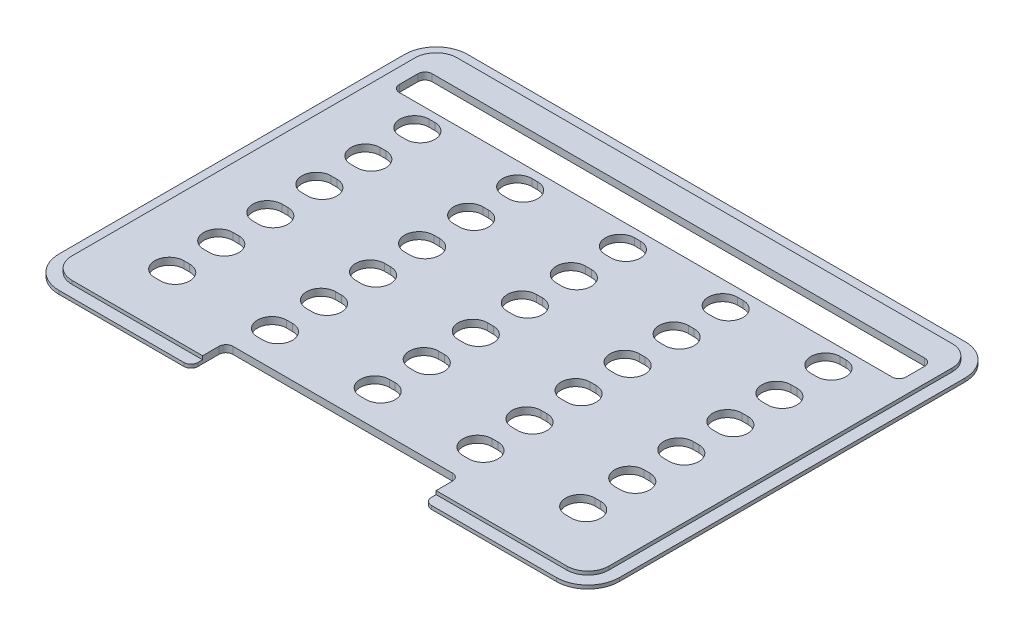
SolidWorks part; units mm, degrees
ref_plane "Front Plane" through (0, 0, 0) normal (0, 0, 1) x (1, 0, 0)
ref_plane "Top Plane" through (0, 0, 0) normal (0, 1, 0) x (1, 0, 0)
ref_plane "Right Plane" through (0, 0, 0) normal (1, 0, 0) x (0, 0, -1)
sketch "Sketch1" plane through (0, 0, 0) normal (0, 1, 0) x (1, 0, 0)
  line L1 (-120, -87.5) -> (120, -87.5)
  line L2 (-120, -87.5) -> (-120, 87.5)
  line L3 (-120, 87.5) -> (120, 87.5)
  line L4 (120, -87.5) -> (120, 87.5)
  line L5 (-120, -87.5) -> (120, 87.5) construction
  line L6 (-120, 87.5) -> (120, -87.5) construction
  point P0 (0, 0)
  dimension "D1" = 240
  dimension "D2" = 175
extrude "Outer Profile" add sketch "Sketch1" along normal blind 1.5
sketch "Sketch2" plane through (0, 1.5, 0) normal (0, 1, 0) x (1, 0, 0)
  line L0 (-120, 87.5) -> (-120, -87.5) construction
  line L1 (-115, -82.5) -> (115, -82.5)
  line L2 (-115, -82.5) -> (-115, 82.5)
  line L3 (-115, 82.5) -> (115, 82.5)
  line L4 (115, -82.5) -> (115, 82.5)
  line L5 (-115, -82.5) -> (115, 82.5) construction
  line L6 (-115, 82.5) -> (115, -82.5) construction
  line L7 (120, 87.5) -> (-120, 87.5) construction
  point P0 (0, 0)
  dimension "D1" = 5
  dimension "D2" = 5
extrude "Inner Profile" add sketch "Sketch2" along normal blind 1.5
fillet "Fillet1" radius 9 4 edges at (115, 2.25, 82.5) (115, 2.25, -82.5) (-115, 2.25, -82.5) (-115, 2.25, 82.5)
fillet "Fillet2" radius 13.5 4 edges at (-120, 0.75, -87.5) (120, 0.75, -87.5) (120, 0.75, 87.5) (-120, 0.75, 87.5)
sketch "Sketch3" plane through (0, 3, 0) normal (0, 1, 0) x (1, 0, 0)
  line L0 (0, 0) -> (0, -50000) construction
  line L1 (-108.5, -67.75) -> (108.5, -67.75) construction
  line L2 (-108.5, -67.75) -> (-108.5, 67.75) construction
  line L3 (-108.5, 67.75) -> (108.5, 67.75) construction
  line L4 (108.5, -67.75) -> (108.5, 67.75) construction
  line L5 (-108.5, -67.75) -> (108.5, 67.75) construction
  line L6 (-108.5, 67.75) -> (108.5, -67.75) construction
  line L7 (-1.25, -57.5) -> (1.25, -57.5) construction
  line L8 (-1.25, -51.25) -> (1.25, -51.25)
  line L9 (-1.25, -63.75) -> (1.25, -63.75)
  line L10 (-106, -82.5) -> (106, -82.5) construction
  arc A0 (-1.25, -51.25) -> (-1.25, -63.75) centre (-1.25, -57.5) ccw
  arc A1 (1.25, -63.75) -> (1.25, -51.25) centre (1.25, -57.5) ccw
  point P0 (0, 0)
  point P5 (0, -57.5)
  point P9 (0, -57.5)
  dimension "D6" = 15
  dimension "D1" = 217
  dimension "D2" = 135.5
  dimension "D3" = 25
  dimension "D5" = 12.5
chamfer "Chamfer" [suppressed] distance 0.5 angle 45
extrude "Cutout" cut sketch "Sketch3" against normal through all
pattern_linear "Cutouts" count 3 spacing 44 along (-1, 0, 0) count 6 spacing 21 along (0, 0, -1) of "Cutout"
mirror "Mirror1" about plane through (0, 0, 0) normal (1, 0, 0) of "Cutouts"
sketch "Sketch4" plane through (0, 3, 0) normal (0, 1, 0) x (1, 0, 0)
  line L0 (0, 82.5) -> (0, 0) construction
  line L1 (-108.5, 57.25) -> (108.5, 57.25)
  line L2 (-108.5, 57.25) -> (-108.5, 71.25)
  line L3 (-108.5, 71.25) -> (108.5, 71.25)
  line L4 (108.5, 57.25) -> (108.5, 71.25)
  line L5 (106, 82.5) -> (-106, 82.5) construction
  line L7 (-108.5, 67.75) -> (108.5, 67.75) construction
  dimension "D1" = 3.5
  dimension "D2" = 14
  dimension "D3" = 217
extrude "Message Window" cut sketch "Sketch4" against normal through all
fillet "Message Window Corners" radius 3 4 edges at (108.5, 1.5, -57.25) (-108.5, 1.5, -57.25) (108.5, 1.5, -71.25) (-108.5, 1.5, -71.25)
sketch "Sketch6" plane through (0, 3, 0) normal (0, 1, 0) x (1, 0, 0)
  line L0 (-106.5, -87.5) -> (106.5, -87.5) construction
  line L1 (-50, -87.5) -> (50, -87.5)
  line L2 (-50, -87.5) -> (-50, -72.5)
  line L3 (-50, -72.5) -> (50, -72.5)
  line L4 (50, -87.5) -> (50, -72.5)
  line L5 (-50, -87.5) -> (50, -72.5) construction
  line L6 (-50, -72.5) -> (50, -87.5) construction
  point P0 (0, -80)
  dimension "D1" = 100
  dimension "D2" = 15
extrude "Base Cutback" cut sketch "Sketch6" against normal through all
fillet "Fillet5" radius 3 4 edges at (-50, 0.75, 87.5) (50, 0.75, 87.5) (50, 1.5, 72.5) (-50, 1.5, 72.5)
chamfer "Edge Chamfer" [suppressed] distance 1 angle 45
